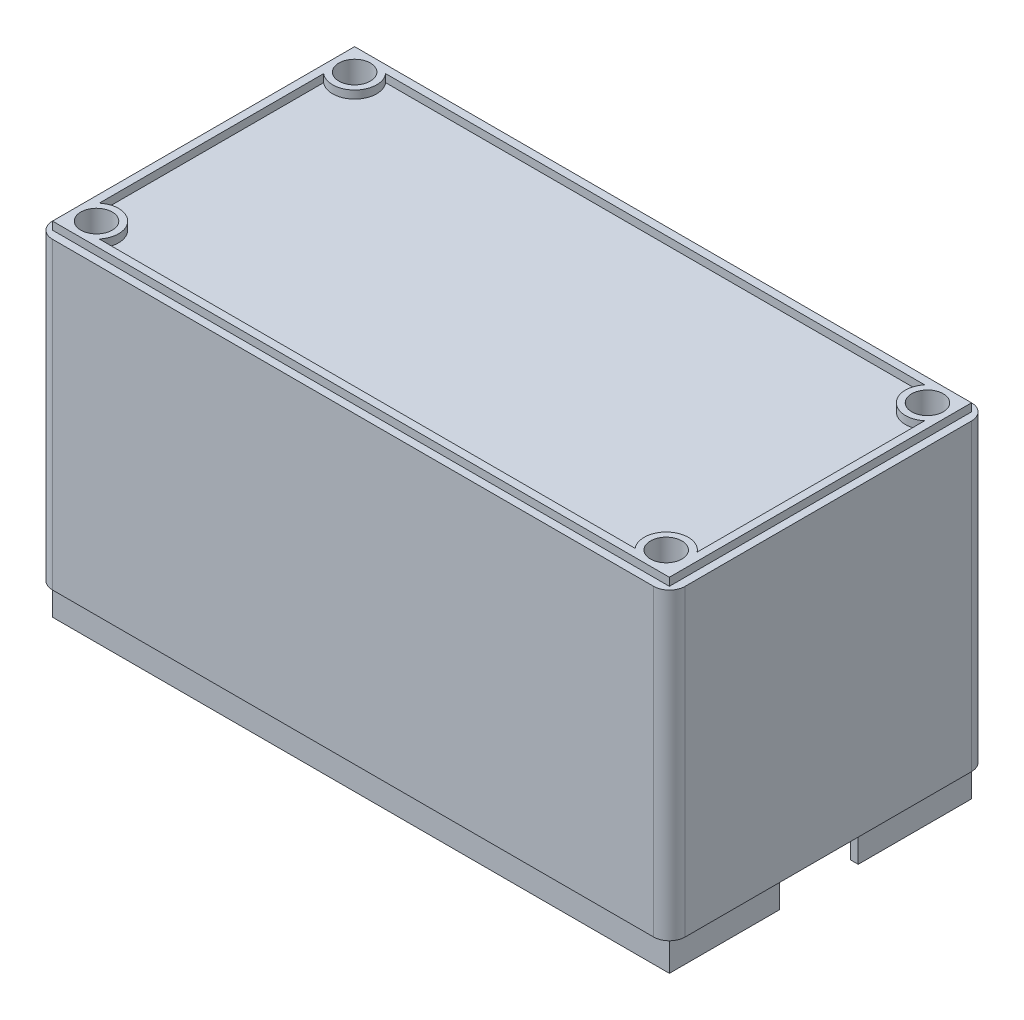
SolidWorks part; units mm, degrees
material "PE Densidad baja/media"
ref_plane "Front Plane" through (0, 0, 0) normal (0, 0, 1) x (1, 0, 0)
ref_plane "Top Plane" through (0, 0, 0) normal (0, 1, 0) x (1, 0, 0)
ref_plane "Right Plane" through (0, 0, 0) normal (1, 0, 0) x (0, 0, -1)
sketch "Sketch1" plane through (0, 0, 0) normal (0, 1, 0) x (1, 0, 0)
  line L0 (-15.9663, 9.9552) -> (-15.9663, -8.2448)
  line L1 (-16.9663, 10.9552) -> (23.2337, 10.9552)
  line L2 (-16.9663, 10.9552) -> (-16.9663, -9.2448)
  line L3 (-16.9663, -9.2448) -> (23.2337, -9.2448)
  line L4 (23.2337, 10.9552) -> (23.2337, -9.2448)
  line L5 (-15.9663, -8.2448) -> (22.2337, -8.2448)
  line L6 (22.2337, 9.9552) -> (22.2337, -8.2448)
  line L7 (-15.9663, 9.9552) -> (22.2337, 9.9552)
  dimension "D1" = 20.2
  dimension "D2" = 40.2
  dimension "D3" = 1
extrude "Boss-Extrude1" add sketch "Sketch1" along normal mid plane 21.3
fillet "Fillet1" radius 1 4 edges at (-16.9663, 0, 9.2448) (-16.9663, 0, -10.9552) (23.2337, 0, -10.9552) (23.2337, 0, 9.2448)
sketch "Sketch2" plane through (0, 10.65, 0) normal (0, 1, 0) x (1, 0, 0)
  line L0 (-16.9663, 9.9552) -> (-16.9663, -8.2448) construction
  line L1 (-16.4663, 10.4552) -> (22.7337, 10.4552)
  line L2 (-16.4663, 10.4552) -> (-16.4663, -8.7448)
  line L3 (-16.4663, -8.7448) -> (22.7337, -8.7448)
  line L4 (22.7337, 10.4552) -> (22.7337, -8.7448)
  line L5 (22.2337, 10.9552) -> (-15.9663, 10.9552) construction
  line L6 (23.2337, -8.2448) -> (23.2337, 9.9552) construction
  line L7 (-15.9663, -9.2448) -> (22.2337, -9.2448) construction
  line L8 (-15.9663, 9.9552) -> (-15.9663, -8.2448)
  line L9 (-15.9663, -8.2448) -> (22.2337, -8.2448)
  line L10 (22.2337, 9.9552) -> (22.2337, -8.2448)
  line L11 (-15.9663, 9.9552) -> (22.2337, 9.9552)
  dimension "D1" = 0.5
  dimension "D2" = 0.5
  dimension "D3" = 0.5
  dimension "D4" = 0.5
  dimension "D5" = 0.5
extrude "Boss-Extrude2" add sketch "Sketch2" along normal blind 0.5
sketch "Sketch3" plane through (0, 10.65, 0) normal (0, 1, 0) x (1, 0, 0)
  line L1 (-15.9663, 9.9552) -> (22.2337, 9.9552)
  line L2 (-15.9663, 9.9552) -> (-15.9663, -8.2448)
  line L3 (-15.9663, -8.2448) -> (22.2337, -8.2448)
  line L4 (22.2337, 9.9552) -> (22.2337, -8.2448)
extrude "Boss-Extrude3" add sketch "Sketch3" against normal blind 1
sketch "Sketch4" plane through (0, 11.15, 0) normal (0, 1, 0) x (1, 0, 0)
  line L0 (-16.4663, 10.4552) -> (-16.4663, -8.7448) construction
  line L1 (22.7337, 10.4552) -> (-16.4663, 10.4552) construction
  line L2 (0, 12.8673) -> (0, -11.566) construction
  line L3 (-16.4663, 10.4552) -> (-16.4663, -8.7448) construction
  line L5 (-16.4663, -8.7448) -> (22.7337, -8.7448) construction
  line L6 (22.7337, 10.4552) -> (-16.4663, 10.4552) construction
  line L7 (22.7337, -8.7448) -> (22.7337, 10.4552) construction
  circle A0 centre (-15.0663, 9.0552) radius 1.4
  circle A1 centre (-15.0663, -7.3448) radius 1.4
  circle A2 centre (21.3337, 9.0552) radius 1.4
  circle A3 centre (21.1337, -7.3448) radius 1.4
  dimension "D1" = 2.8
  dimension "D2" = 2.8
  dimension "D3" = 2.8
  dimension "D4" = 2.8
extrude "Boss-Extrude4" add sketch "Sketch4" against normal up to surface (21.8 mm away)
sketch "Sketch5" plane through (0, 11.15, 0) normal (0, 1, 0) x (1, 0, 0)
  circle A0 centre (-15.0663, 9.0552) radius 1
  circle A1 centre (-15.0663, -7.3448) radius 1
  circle A2 centre (21.3337, 9.0552) radius 1
  circle A3 centre (21.1337, -7.3448) radius 1
  arc A4 (22.2337, -6.4788) -> (20.0613, -8.2448) centre (21.1337, -7.3448) ccw construction
extrude "Cut-Extrude1" cut sketch "Sketch5" against normal through all
sketch "Sketch6" plane through (0, -10.65, 0) normal (0, -1, 0) x (1, 0, 0)
  line L0 (-16.9663, -9.9552) -> (-16.9663, 8.2448) construction
  line L1 (-16.4663, 8.7448) -> (22.7337, 8.7448)
  line L2 (-16.4663, 8.7448) -> (-16.4663, -10.4552)
  line L3 (-16.4663, -10.4552) -> (22.7337, -10.4552)
  line L4 (22.7337, 8.7448) -> (22.7337, -10.4552)
  line L5 (-15.9663, 9.2448) -> (22.2337, 9.2448) construction
  line L6 (23.2337, 8.2448) -> (23.2337, -9.9552) construction
  line L7 (22.2337, -10.9552) -> (-15.9663, -10.9552) construction
  line L8 (-16.9663, 9.2448) -> (-16.9663, -10.9552)
  line L9 (-16.9663, -10.9552) -> (23.2337, -10.9552)
  line L10 (23.2337, 9.2448) -> (23.2337, -10.9552)
  line L11 (-16.9663, 9.2448) -> (23.2337, 9.2448)
  dimension "D1" = 0.5
  dimension "D2" = 0.5
  dimension "D3" = 0.5
  dimension "D4" = 0.5
  dimension "D5" = 0.5
extrude "Cut-Extrude2" cut sketch "Sketch6" against normal blind 2
sketch "Sketch7" plane through (22.7337, 0, 0) normal (1, 0, 0) x (0, 0, -1)
  line L0 (9.9552, -8.65) -> (-8.2448, -8.65) construction
  line L1 (-1.7448, -8.65) -> (3.2552, -8.65)
  line L2 (-1.7448, -8.65) -> (-1.7448, -10.65)
  line L3 (-1.7448, -10.65) -> (3.2552, -10.65)
  line L4 (3.2552, -8.65) -> (3.2552, -10.65)
  line L5 (-1.7448, -10) -> (-1.7448, -8) construction
  line L6 (10.4552, -10.65) -> (-8.7448, -10.65) construction
  line L7 (3.2552, -10) -> (3.2552, -8) construction
extrude "Cut-Extrude3" cut sketch "Sketch7" against normal up to surface (0.5 mm away) up to face at (22.2337, -0.5, -0.752)
